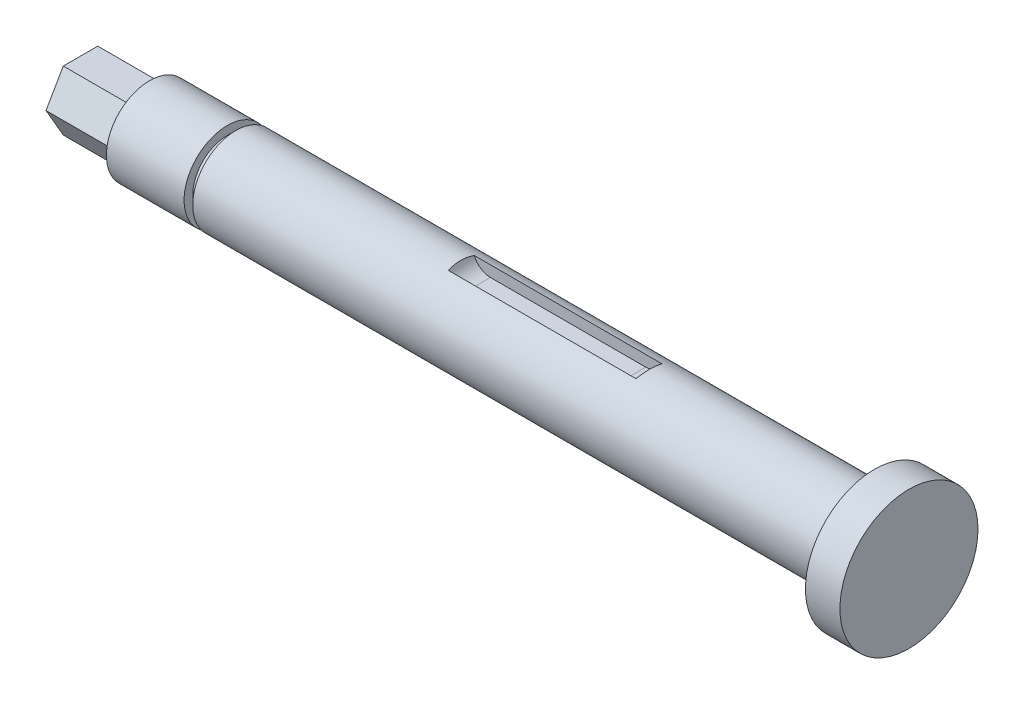
SolidWorks part; units mm, degrees
material "Chrome Stainless Steel"
ref_plane "Front Plane" through (0, 0, 0) normal (0, 0, 1) x (1, 0, 0)
ref_plane "Top Plane" through (0, 0, 0) normal (0, 1, 0) x (1, 0, 0)
ref_plane "Right Plane" through (0, 0, 0) normal (1, 0, 0) x (0, 0, -1)
sketch "Sketch1" plane through (0, 0, 0) normal (0, 0, 1) x (1, 0, 0)
  line L0 (0, 0) -> (-17.5543, 0) construction
  line L1 (0, 0) -> (0, 6.35)
  line L2 (0, 6.35) -> (12.7, 6.35)
  line L3 (12.7, 6.35) -> (12.7, 7.9375)
  line L4 (12.7, 7.9375) -> (26.9875, 7.9375)
  line L5 (26.9875, 7.9375) -> (26.9875, 6.35)
  line L6 (26.9875, 6.35) -> (28.575, 6.35)
  line L7 (28.575, 6.35) -> (28.575, 7.9375)
  line L8 (28.575, 7.9375) -> (146.05, 7.9375)
  line L9 (146.05, 7.9375) -> (146.05, 12.7)
  line L10 (146.05, 12.7) -> (152.4, 12.7)
  line L11 (152.4, 12.7) -> (152.4, 0)
  line L12 (152.4, 0) -> (0, 0)
  dimension "D1" = 12.7
  dimension "D2" = 25.4
  dimension "D3" = 15.875
  dimension "D4" = 1.5875
  dimension "D5" = 1.5875
  dimension "D6" = 6.35
  dimension "D7" = 117.475
  dimension "D8" = 12.7
  dimension "D9" = 133.35
revolve "Base" add sketch "Sketch1" angle 360 about L0
sketch "Sketch2" plane through (0, 0, 0) normal (0, 0, 1) x (1, 0, 0)
  line L0 (69.85, 14.2875) -> (69.85, 8.7249)
  line L1 (73.025, 5.5499) -> (101.6, 5.5499)
  line L2 (104.775, 8.7249) -> (104.775, 14.2875)
  line L3 (104.775, 14.2875) -> (69.85, 14.2875)
  line L4 (146.05, 7.9375) -> (28.575, 7.9375) construction
  arc A0 (69.85, 8.7249) -> (73.025, 5.5499) centre (73.025, 8.7249) ccw
  arc A1 (101.6, 5.5499) -> (104.775, 8.7249) centre (101.6, 8.7249) ccw
  point P11 (69.85, 11.5062)
  dimension "D3" = 3.175
  dimension "D1" = 2.3876
  dimension "D2" = 34.925
  dimension "D4" = 6.35
  dimension "D5" = 69.85
extrude "Cut-Extrude1" cut sketch "Sketch2" against normal mid plane 4.7625
sketch "Sketch3" plane through (0, 0, 0) normal (-1, 0, 0) x (0, 0, 1)
  line L1 (3.175, 5.4993) -> (-3.175, 5.4993)
  line L2 (-3.175, 5.4993) -> (-6.35, 0)
  line L3 (-6.35, 0) -> (-3.175, -5.4993)
  line L4 (-3.175, -5.4993) -> (3.175, -5.4993)
  line L5 (3.175, -5.4993) -> (6.35, 0)
  line L6 (6.35, 0) -> (3.175, 5.4993)
  circle A0 centre (0, 0) radius 6.35 construction
  circle A1 centre (0, 0) radius 6.35 construction
extrude "Cut-Extrude2" cut sketch "Sketch3" against normal up to surface (12.7 mm away) flip side to cut up to face at (12.7, 0, -6.35)
